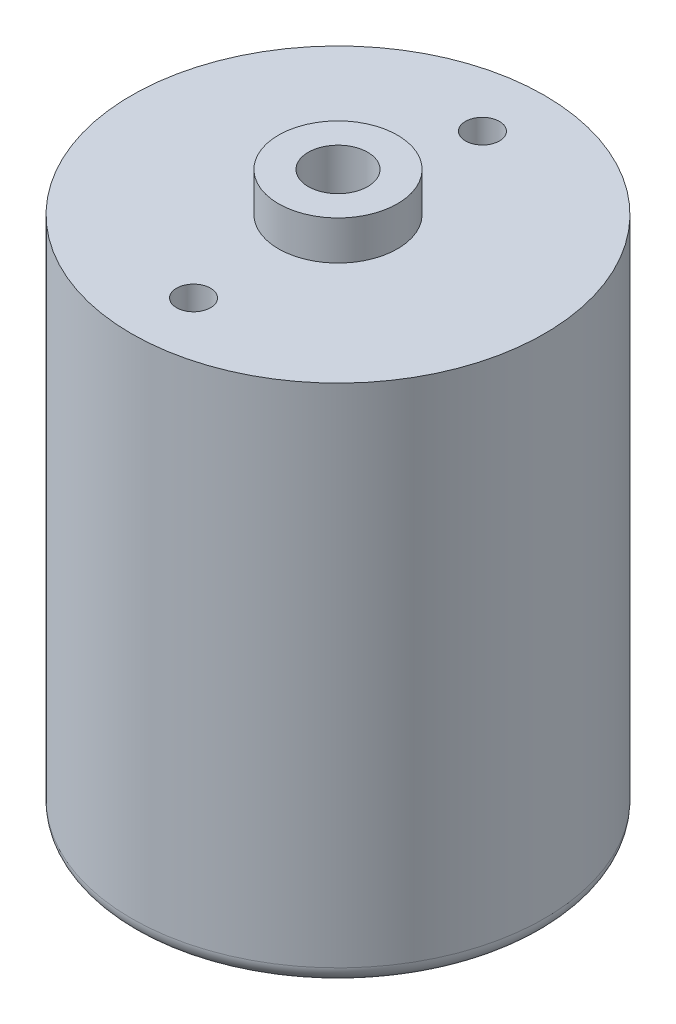
SolidWorks part; units mm, degrees
ref_plane "前视基准面" through (0, 0, 0) normal (0, 0, 1) x (1, 0, 0)
ref_plane "上视基准面" through (0, 0, 0) normal (0, 1, 0) x (1, 0, 0)
ref_plane "右视基准面" through (0, 0, 0) normal (1, 0, 0) x (0, 0, -1)
sketch "草图1" plane through (0, 0, 0) normal (0, 1, 0) x (1, 0, 0)
  circle A0 centre (0, 0) radius 12.15
  dimension "D1" = 24.3
extrude "凸台-拉伸1" add sketch "草图1" along normal blind 30.8
fillet "圆角1" radius 1 1 edges at (0, 0, 12.15)
sketch "草图2" plane through (0, 30.8, 0) normal (0, 1, 0) x (1, 0, 0)
  line L0 (0, 0) -> (-15.8805, 0) construction
  line L1 (-15.8805, 0) -> (22.8313, 0) construction
  line L2 (0, 0) -> (0, 12.7733) construction
  line L3 (0, 12.7733) -> (0, -13.3104) construction
  circle A0 centre (0, 8.5) radius 1
  circle A1 centre (0, -8.5) radius 1
  circle A2 centre (0, 0) radius 3.5
  dimension "D2" = 2
  dimension "D3" = 2
  dimension "D4" = 7
  dimension "D1" = 17
  dimension "D5" = 8.5
  dimension "D6" = 90
extrude "凸台-拉伸2" add sketch "草图2" along normal blind 2.3 and the other way blind 30.8 contours A2 | A1
sketch "草图3" plane through (0, 30.8, 0) normal (0, 1, 0) x (1, 0, 0)
  line L0 (-16.0799, 0) -> (21.4511, 0) construction
  line L1 (21.4511, 0) -> (0, 0) construction
  line L2 (0, 0) -> (0, 13.0419) construction
  line L3 (0, 13.0419) -> (0, -13.2433) construction
  circle A0 centre (0, 8.5) radius 1
  circle A1 centre (0, -8.5) radius 1
  dimension "D3" = 2
  dimension "D4" = 2
  dimension "D1" = 17
  dimension "D2" = 8.5
extrude "切除-拉伸1" cut sketch "草图3" against normal through all
sketch "草图4" plane through (0, 33.1, 0) normal (0, 1, 0) x (1, 0, 0)
  circle A0 centre (0, 0) radius 1.75
  dimension "D1" = 3.5
extrude "切除-拉伸2" cut sketch "草图4" against normal through all
